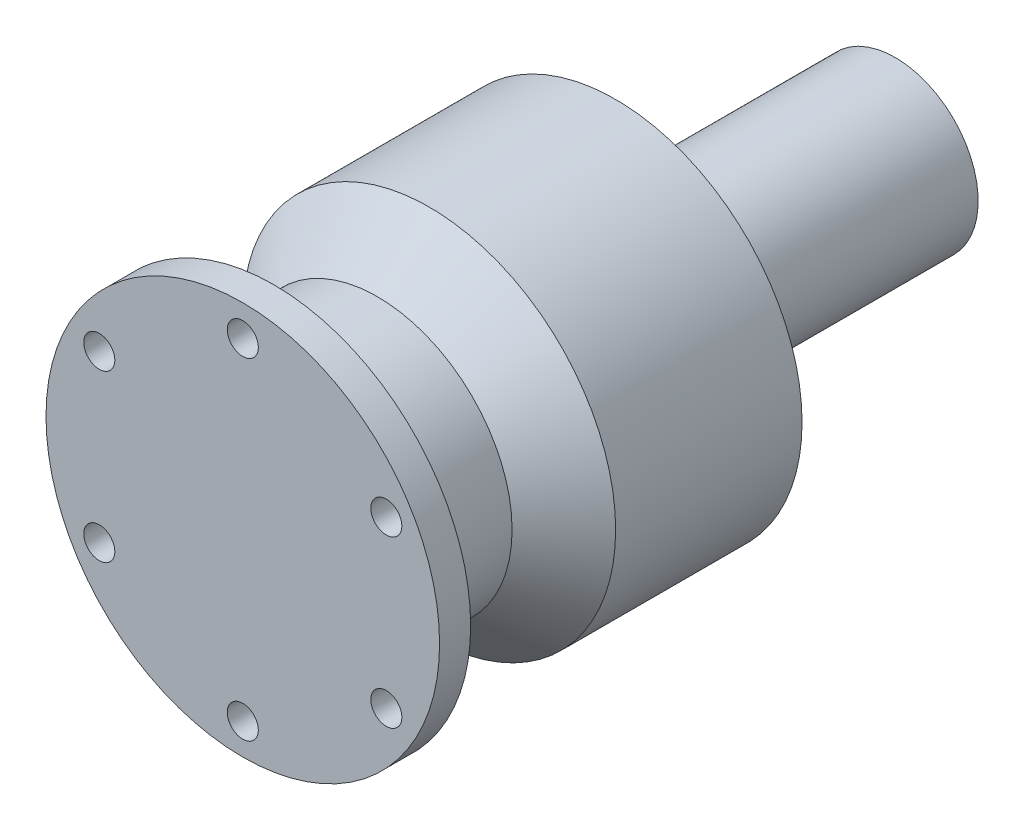
SolidWorks part; units mm, degrees
ref_plane "Front Plane" through (0, 0, 0) normal (0, 0, 1) x (1, 0, 0)
ref_plane "Top Plane" through (0, 0, 0) normal (0, 1, 0) x (1, 0, 0)
ref_plane "Right Plane" through (0, 0, 0) normal (1, 0, 0) x (0, 0, -1)
sketch "Croquis2" plane through (0, 0, 0) normal (0, 0, 1) x (1, 0, 0)
  circle A0 centre (0, 0) radius 18
extrude "Saliente-Extruir1" add sketch "Croquis2" along normal blind 30
sketch "Croquis3" plane through (0, 0, 30) normal (0, 0, 1) x (1, 0, 0)
  circle A0 centre (0, 0) radius 13
extrude "Saliente-Extruir3" add sketch "Croquis3" along normal blind 10
sketch "Croquis5" plane through (0, 0, 0) normal (0, 0, -1) x (-1, 0, 0)
  circle A0 centre (0, 0) radius 8
extrude "Saliente-Extruir4" add sketch "Croquis5" along normal blind 20
sketch "Croquis6" plane through (0, 0, 30) normal (0, 0, 1) x (1, 0, 0)
  circle A0 centre (0, 0) radius 13
extrude "Cortar-Extruir2" cut sketch "Croquis6" against normal blind 8 draft 45 flip side to cut
sketch "Croquis7" plane through (0, 0, 0) normal (0, 0, -1) x (-1, 0, 0)
  circle A0 centre (0, 0) radius 8
extrude "Cortar-Extruir5" cut sketch "Croquis7" against normal blind 8 draft 55 flip side to cut
sketch "Croquis8" plane through (0, 0, 40) normal (0, 0, 1) x (1, 0, 0)
  circle A0 centre (0, 0) radius 19
extrude "Saliente-Extruir5" add sketch "Croquis8" along normal blind 3
sketch "Croquis9" plane through (0, 0, 43) normal (0, 0, 1) x (1, 0, 0)
  circle A0 centre (0, 16) radius 1.5
  circle A1 centre (13.8564, 8) radius 1.5
  circle A2 centre (13.8564, -8) radius 1.5
  circle A3 centre (0, -16) radius 1.5
  circle A4 centre (-13.8564, -8) radius 1.5
  circle A5 centre (-13.8564, 8) radius 1.5
  point P15 (0, 0)
  dimension "D1" = 6
extrude "Cortar-Extruir6" cut sketch "Croquis9" against normal blind 3
